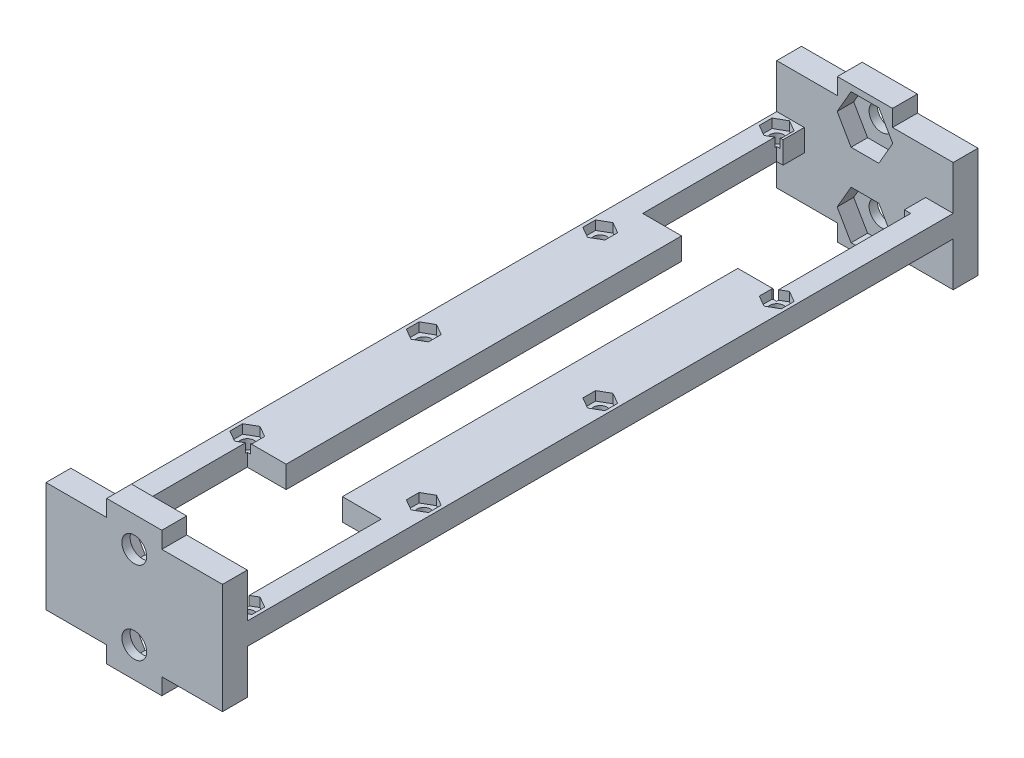
SolidWorks part; units mm, degrees
ref_plane "Front Plane" through (0, 0, 0) normal (0, 0, 1) x (1, 0, 0)
ref_plane "Top Plane" through (0, 0, 0) normal (0, 1, 0) x (1, 0, 0)
ref_plane "Right Plane" through (0, 0, 0) normal (1, 0, 0) x (0, 0, -1)
sketch "Sketch1" plane through (0, 0, 0) normal (0, 1, 0) x (1, 0, 0)
  line L1 (16, 64) -> (-16, 64)
  line L2 (16, 64) -> (16, -64)
  line L3 (16, -64) -> (-16, -64)
  line L4 (-16, 64) -> (-16, -64)
  line L5 (16, 64) -> (-16, -64) construction
  line L6 (16, -64) -> (-16, 64) construction
  point P0 (0, 0)
  dimension "D1" = 32
  dimension "D2" = 128
extrude "Boss-Extrude1" add sketch "Sketch1" along normal blind 4
sketch "Sketch4" plane through (0, 0, 0) normal (0, -1, 0) x (1, 0, 0)
  line L0 (-16, 64) -> (16, 64) construction
  line L1 (16, 64) -> (16, -64) construction
  circle A0 centre (13.4, 61.4) radius 1.25
  dimension "D1" = 2.5
  dimension "D2" = 2.6
  dimension "D3" = 2.6
extrude "Cut-Extrude2" cut sketch "Sketch4" against normal blind 10
sketch "Sketch5" plane through (0, 0, 0) normal (0, -1, 0) x (1, 0, 0)
  line L1 (16, -64) -> (-16, -64) construction
  line L2 (-16, -64) -> (-16, 64) construction
  circle A0 centre (-13.4, -61.4) radius 1.25
  dimension "D1" = 2.5
  dimension "D2" = 2.6
  dimension "D3" = 2.6
extrude "Cut-Extrude3" cut sketch "Sketch5" against normal blind 10
sketch "Sketch6" plane through (0, 4, 0) normal (0, 1, 0) x (1, 0, 0)
  line L0 (-15.4005, 62.555) -> (-13.4, 63.71)
  line L1 (-13.4, 63.71) -> (-11.3995, 62.555)
  line L2 (-11.3995, 62.555) -> (-11.3995, 60.245)
  line L3 (-11.3995, 60.245) -> (-13.4, 59.09)
  line L4 (-13.4, 59.09) -> (-15.4005, 60.245)
  line L5 (-15.4005, 60.245) -> (-15.4005, 62.555)
  line L6 (-13.4, 63.71) -> (-13.4, 59.09) construction
  point P4 (-13.4, 61.4)
  point P7 (-13.4, 61.4)
  dimension "D1" = 2.31
  dimension "D2" = 120
  dimension "D3" = 120
extrude "Cut-Extrude4" cut sketch "Sketch6" against normal blind 1.65
pattern_linear "LPattern3" count 4 spacing 32 along (0, 0, 1) of "Cut-Extrude3", "Cut-Extrude4"
sketch "Sketch7" plane through (0, 4, 0) normal (0, 1, 0) x (1, 0, 0)
  line L0 (13.4, -59.09) -> (11.3995, -60.245)
  line L1 (11.3995, -60.245) -> (11.3995, -62.555)
  line L2 (11.3995, -62.555) -> (13.4, -63.71)
  line L3 (13.4, -63.71) -> (15.4005, -62.555)
  line L4 (15.4005, -62.555) -> (15.4005, -60.245)
  line L5 (15.4005, -60.245) -> (13.4, -59.09)
  line L6 (13.4, -59.09) -> (13.4, -63.71) construction
  point P0 (13.4, -61.4)
  point P8 (13.4, -61.4)
  dimension "D1" = 120
  dimension "D2" = 120
  dimension "D3" = 2.31
extrude "Cut-Extrude5" cut sketch "Sketch7" against normal blind 1.65
pattern_linear "LPattern4" count 4 spacing 32 along (0, 0, -1) of "Cut-Extrude5", "Cut-Extrude2"
sketch "Sketch8" plane through (0, 0, 0) normal (0, -1, 0) x (1, 0, 0)
  line L0 (12.15, 61.4) -> (12.15, 31.9812) construction
  line L1 (13.4, 60.15) -> (-14.2218, 60.15) construction
  line L2 (-13.4, 35.85) -> (12.15, 35.85) construction
  line L4 (-12.15, 60.15) -> (12.15, 60.15)
  line L5 (-12.15, 34.6) -> (-12.15, 60.15) construction
  line L6 (-12.15, 60.15) -> (-12.15, 35.85)
  line L7 (-12.15, 35.85) -> (12.15, 35.85)
  line L8 (12.15, 60.15) -> (12.15, 35.85)
  circle A2 centre (13.4, 61.4) radius 1.25 construction
  circle A3 centre (-13.4, 34.6) radius 1.25 construction
extrude "Cut-Extrude6" cut sketch "Sketch8" against normal blind 10
mirror "Mirror1" about plane through (0, 0, 0) normal (0, 0, 1) of "Cut-Extrude6"
sketch "Sketch9" plane through (0, 0, -64) normal (0, 0, -1) x (-1, 0, 0)
  line L0 (0, 0) -> (0, 4) construction
  line L1 (-16, 0) -> (16, 0) construction
  line L2 (-16, 4) -> (16, 4) construction
  line L3 (-16, 2) -> (16, 2) construction
  line L4 (-16, 4) -> (-16, 0) construction
  line L5 (16, 4) -> (16, 0) construction
  line L6 (-16, 12) -> (-5, 12)
  line L8 (16, -8) -> (16, 12)
  line L10 (-16, -8) -> (-16, 12)
  line L11 (16, -8) -> (-16, 12) construction
  line L12 (16, 12) -> (-16, -8) construction
  line L13 (-5, 12) -> (-5, 15)
  line L14 (-5, 15) -> (5, 15)
  line L15 (5, 15) -> (5, 12)
  line L16 (5, 12) -> (16, 12)
  line L17 (-16, -8) -> (-5, -8)
  line L18 (-5, -8) -> (-5, -11)
  line L19 (-5, -11) -> (5, -11)
  line L20 (5, -11) -> (5, -8)
  line L21 (5, -8) -> (16, -8)
  point P12 (0, 2)
  dimension "D1" = 32
  dimension "D2" = 20
  dimension "D3" = 10
  dimension "D4" = 3
  dimension "D5" = 3
extrude "Boss-Extrude2" add sketch "Sketch9" along normal blind 4.5
sketch "Sketch11" plane through (0, 0, 0) normal (0, -1, 0) x (1, 0, 0)
  line L0 (-5.1, 35.85) -> (-5.1, -35.85)
  line L1 (-12.15, 35.85) -> (12.15, 35.85) construction
  line L2 (-12.15, -35.85) -> (12.15, -35.85) construction
  line L3 (-5.1, -35.85) -> (5.1, -35.85)
  line L4 (5.1, -35.85) -> (5.1, 35.85)
  line L5 (5.1, 35.85) -> (-5.1, 35.85)
  point P6 (0, 35.85)
  dimension "D1" = 10.2
extrude "Cut-Extrude7" cut sketch "Sketch11" against normal through all
sketch "Sketch10" plane through (0, 0, -64) normal (0, 0, 1) x (1, 0, 0)
  line L0 (-2.52, 13.8648) -> (2.52, 13.8648)
  line L1 (2.52, 13.8648) -> (5.04, 9.5)
  line L2 (5.04, 9.5) -> (2.52, 5.1352)
  line L3 (2.52, 5.1352) -> (-2.52, 5.1352)
  line L4 (-2.52, 5.1352) -> (-5.04, 9.5)
  line L5 (-5.04, 9.5) -> (-2.52, 13.8648)
  line L6 (-5.04, 9.5) -> (5.04, 9.5) construction
  line L7 (0, 13.8648) -> (0, 4.395) construction
  line L14 (-16, 2) -> (16, 2) construction
  line L15 (-16, 4) -> (-16, 0) construction
  line L16 (16, 4) -> (16, 0) construction
  point P7 (0, 2)
  point P8 (0, 5.1352)
  point P11 (0, 9.5)
  dimension "D1" = 120
  dimension "D2" = 120
  dimension "D3" = 5.04
  dimension "D4" = 7.5
extrude "Cut-Extrude8" cut sketch "Sketch10" against normal blind 3
sketch "Sketch12" plane through (0, 0, -67) normal (0, 0, 1) x (1, 0, 0)
  line L0 (-5.04, 9.5) -> (5.04, 9.5) construction
  circle A0 centre (0, 9.5) radius 2.25
  point P6 (0, 9.5)
  dimension "D1" = 4.5
extrude "Cut-Extrude9" cut sketch "Sketch12" against normal blind 3
ref_plane "midplane" through (0, 2, 0) normal (0, 1, 0) x (1, 0, 0)
mirror "Mirror2" about plane through (0, 2, 0) normal (0, 1, 0) of "Cut-Extrude9", "Cut-Extrude8"
mirror "Mirror3" about plane through (0, 0, 0) normal (0, 0, 1) of "Cut-Extrude8", "Cut-Extrude9", "Mirror2", "Boss-Extrude2"
sketch "Sketch14" plane through (0, 0, 0) normal (0, -1, 0) x (1, 0, 0)
  line L0 (-16, 64) -> (16, 64) construction
  line L1 (-11, 60.15) -> (11, 60.15)
  line L2 (-11, 60.15) -> (-11, 64)
  line L3 (-11, 64) -> (11, 64)
  line L4 (11, 60.15) -> (11, 64)
  line L5 (-16, 64) -> (16, 64) construction
  line L8 (11.564, 60.15) -> (-12.15, 60.15) construction
  line L9 (0, 0) -> (0, 69.5714) construction
  point P9 (0, 64)
  dimension "D1" = 22
extrude "Cut-Extrude13" cut sketch "Sketch14" against normal blind 10
mirror "Mirror4" about plane through (0, 0, 0) normal (0, 0, 1) of "Cut-Extrude13"
